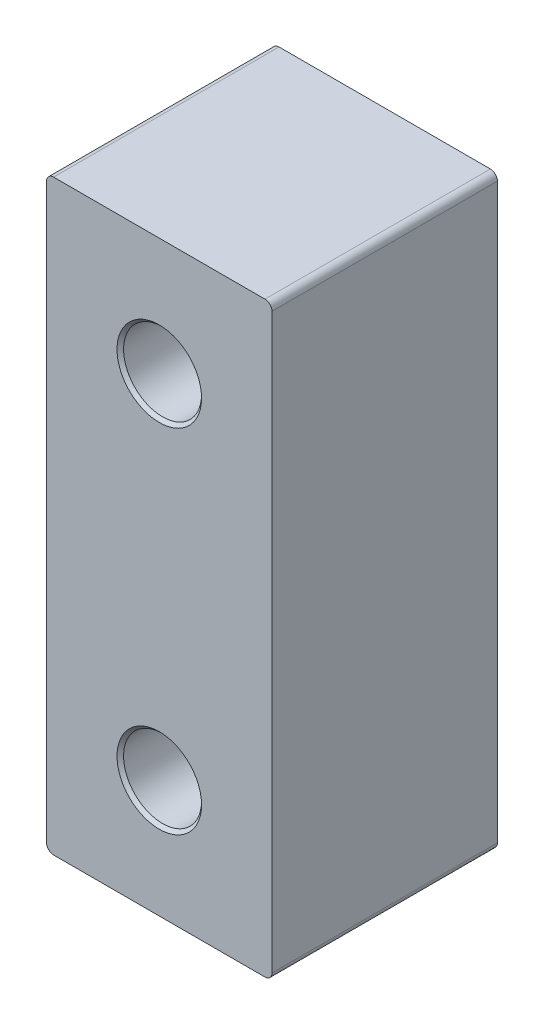
SolidWorks part; units mm, degrees
material "ASTM A36 Steel"
ref_plane "Front Plane" through (0, 0, 0) normal (0, 0, 1) x (1, 0, 0)
ref_plane "Top Plane" through (0, 0, 0) normal (0, 1, 0) x (1, 0, 0)
ref_plane "Right Plane" through (0, 0, 0) normal (1, 0, 0) x (0, 0, -1)
sketch "Sketch1" plane through (0, 0, 0) normal (0, 0, 1) x (1, 0, 0)
  line L1 (-6.096, 15.875) -> (6.096, 15.875)
  line L2 (-6.096, 15.875) -> (-6.096, -15.875)
  line L3 (-6.096, -15.875) -> (6.096, -15.875)
  line L4 (6.096, 15.875) -> (6.096, -15.875)
  point P4 (6.096, 0)
  point P5 (0, 15.875)
  dimension "D1" = 31.75
  dimension "D2" = 12.192
extrude "Boss-Extrude1" add sketch "Sketch1" along normal blind 12.192
fillet "Fillet1" radius 0.381 4 edges at (-6.096, 15.875, 6.096) (-6.096, -15.875, 6.096) (6.096, 15.875, 6.096) (6.096, -15.875, 6.096)
hole_wizard "#19 (0.166) Diameter Hole1" positions "Sketch3" profile "Sketch2" hole size "#19" standard "ANSI Inch" end condition through all
sketch "Sketch3" plane through (0, 0, 12.192) normal (0, 0, 1) x (1, 0, 0)
  point P0 (0, 9.525)
  point P2 (0, -9.525)
  dimension "D1" = 9.525
  dimension "D2" = 9.525
sketch "Sketch2" plane through (0, 9.525, 12.192) normal (1, 0, 0) x (0, -1, 0)
  line L0 (0, 0) -> (0, 12.192)
  line L1 (0, 12.192) -> (2.286, 12.192)
  line L2 (2.1082, 12.0142) -> (2.1082, 0.1778)
  line L3 (2.1082, 0.1778) -> (2.286, 0)
  line L5 (2.286, 0) -> (0, 0)
  line L6 (-2.1082, 0.1778) -> (-2.286, 0) construction
  line L7 (2.286, 12.192) -> (2.1082, 12.0142)
  line L8 (-2.286, 12.192) -> (-2.1082, 12.0142) construction
  line L11 (0, -6.35) -> (0, 107.95) construction
  dimension "Thru Hole Dia." = 4.2164
  dimension "Thru Hole Depth" = 12.192
  dimension "Near C'Sink Dia." = 4.572
  dimension "Near C'Sink Angle" = 90
  dimension "Far C'Sink Dia." = 4.572
  dimension "Far C'Sink Angle" = 90
pattern_linear "LPattern1" [suppressed] count 4 spacing 41.91
